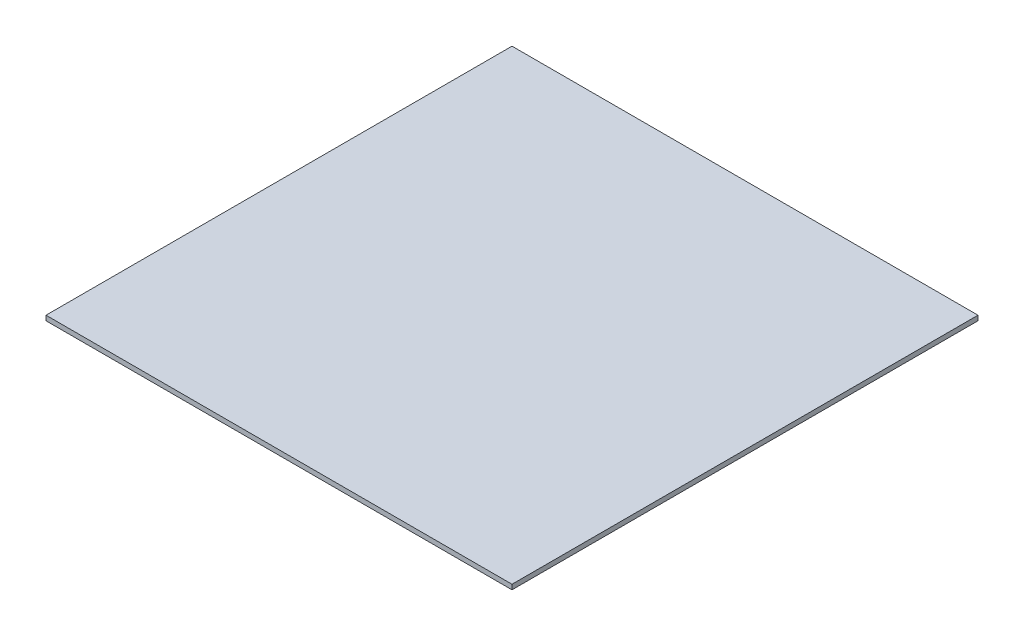
SolidWorks part; units mm, degrees
ref_plane "Front Plane" through (0, 0, 0) normal (0, 0, 1) x (1, 0, 0)
ref_plane "Top Plane" through (0, 0, 0) normal (0, 1, 0) x (1, 0, 0)
ref_plane "Right Plane" through (0, 0, 0) normal (1, 0, 0) x (0, 0, -1)
sketch "Sketch1" plane through (0, 0, 0) normal (0, 1, 0) x (1, 0, 0)
  line L1 (-44.6214, 273.1636) -> (260.1786, 273.1636)
  line L2 (-44.6214, 273.1636) -> (-44.6214, -31.6364)
  line L3 (-44.6214, -31.6364) -> (260.1786, -31.6364)
  line L4 (260.1786, 273.1636) -> (260.1786, -31.6364)
extrude "Boss-Extrude1" add sketch "Sketch1" along normal blind 3.175 contours L2 L1 L4 L3
